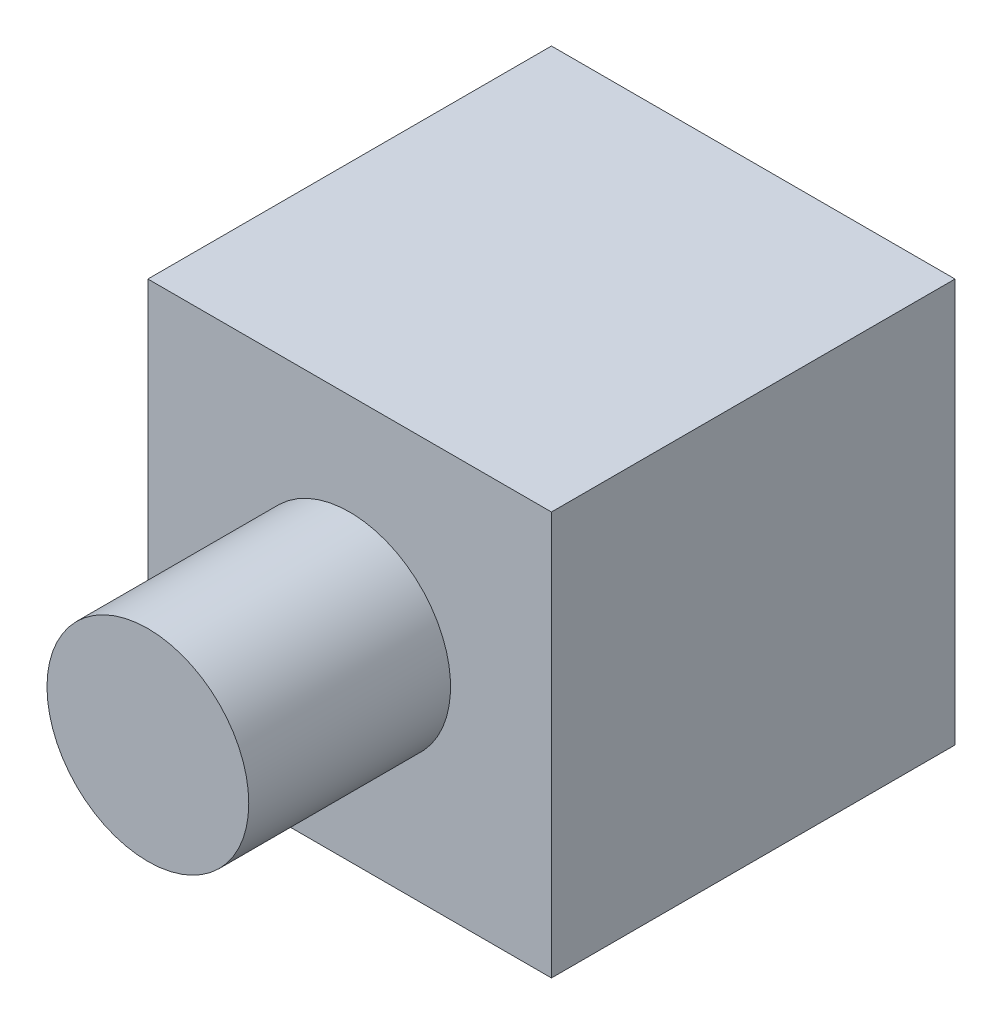
SolidWorks part; units mm, degrees
material "1060 Alloy"
ref_plane "Front Plane" through (0, 0, 0) normal (0, 0, 1) x (1, 0, 0)
ref_plane "Top Plane" through (0, 0, 0) normal (0, 1, 0) x (1, 0, 0)
ref_plane "Right Plane" through (0, 0, 0) normal (1, 0, 0) x (0, 0, -1)
sketch "Sketch1" plane through (0, 0, 0) normal (0, 0, 1) x (1, 0, 0)
  line L1 (-25.4, -25.4) -> (25.4, -25.4)
  line L2 (-25.4, -25.4) -> (-25.4, 25.4)
  line L3 (-25.4, 25.4) -> (25.4, 25.4)
  line L4 (25.4, -25.4) -> (25.4, 25.4)
  line L5 (-25.4, -25.4) -> (25.4, 25.4) construction
  line L6 (-25.4, 25.4) -> (25.4, -25.4) construction
  point P0 (0, 0)
  dimension "D1" = 50.8
extrude "Boss-Extrude1" add sketch "Sketch1" along normal blind 50.8
sketch "Sketch2" plane through (0, 0, 50.8) normal (0, 0, 1) x (1, 0, 0)
  circle A0 centre (0, 0) radius 12.7
  dimension "D1" = 25.4
extrude "Boss-Extrude2" add sketch "Sketch2" along normal blind 25.4
sketch "Sketch3" plane through (0, 0, 0) normal (0, 0, -1) x (-1, 0, 0)
  circle A0 centre (0, 0) radius 12.7
  dimension "D1" = 25.4
extrude "Cut-Extrude1" cut sketch "Sketch3" against normal blind 25.4
